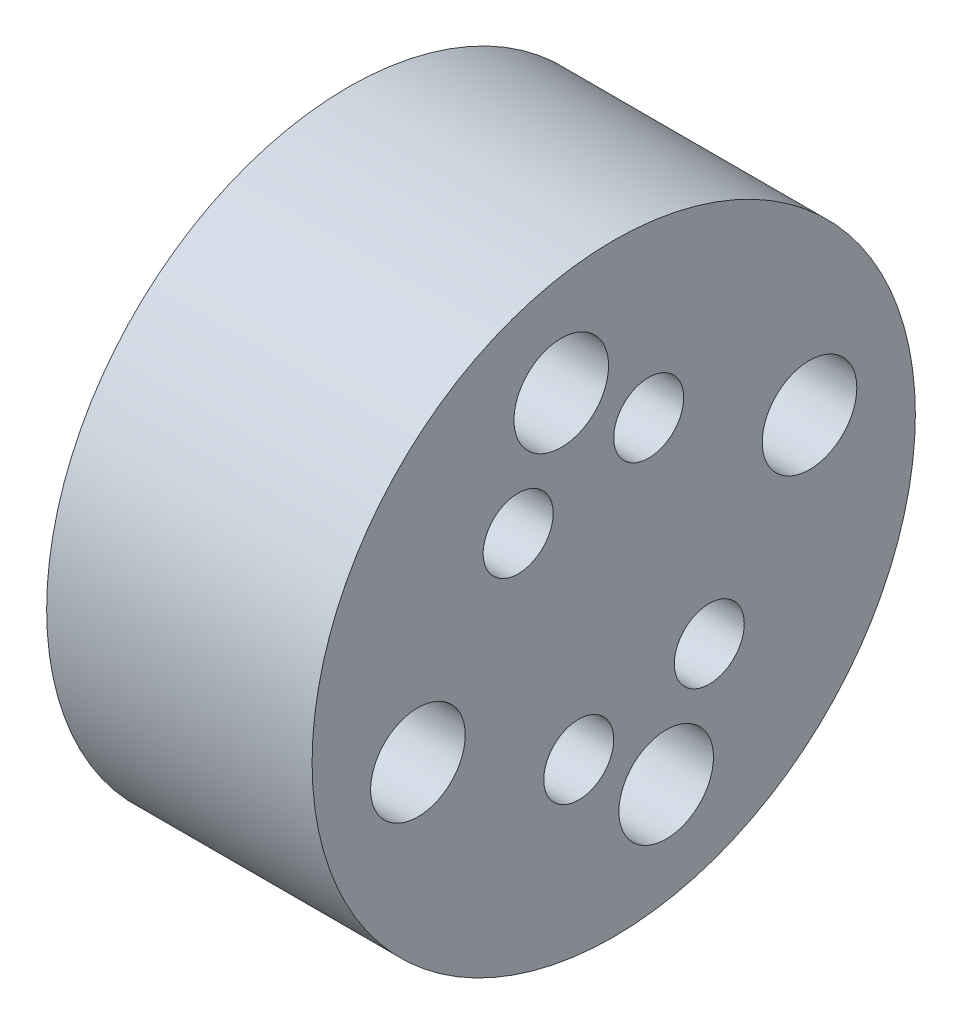
SolidWorks part; units mm, degrees
material "PLA"
ref_plane "Front Plane" through (0, 0, 0) normal (0, 0, 1) x (1, 0, 0)
ref_plane "Top Plane" through (0, 0, 0) normal (0, 1, 0) x (1, 0, 0)
ref_plane "Right Plane" through (0, 0, 0) normal (1, 0, 0) x (0, 0, -1)
sketch "Sketch1" plane through (0, 0, 0) normal (1, 0, 0) x (0, 0, -1)
  circle A0 centre (0, 0) radius 31.25
  dimension "D1" = 62.5
extrude "Boss-Extrude1" add sketch "Sketch1" along normal blind 23
sketch "Sketch6" plane through (23, 0, 0) normal (1, 0, 0) x (0, 0, -1)
  line L0 (-5.4352, 20.2844) -> (0, 0) construction
  line L1 (0, 0) -> (0, 21) construction
  circle A0 centre (0, 0) radius 21 construction
  circle A1 centre (-5.4352, 20.2844) radius 4
  circle A2 centre (0, 0) radius 21 construction
  circle A3 centre (20.2844, 5.4352) radius 4
  circle A4 centre (0, 0) radius 21 construction
  circle A5 centre (5.4352, -20.2844) radius 4
  circle A6 centre (0, 0) radius 21 construction
  circle A7 centre (-20.2844, -5.4352) radius 4
  point P18 (0, 0)
  dimension "D1" = 42
  dimension "D2" = 8
  dimension "D3" = 15
  dimension "D4" = 4
extrude "Cut-Extrude3" cut sketch "Sketch6" against normal through all
sketch "Sketch7" plane through (23, 0, 0) normal (1, 0, 0) x (0, 0, -1)
  circle A0 centre (-5.4352, 20.2844) radius 4.9
  circle A1 centre (20.2844, 5.4352) radius 4.9
  circle A2 centre (5.4352, -20.2844) radius 4.9
  circle A3 centre (-20.2844, -5.4352) radius 4.9
  dimension "D1" = 9.8
  dimension "D2" = 9.8
  dimension "D3" = 9.8
  dimension "D4" = 9.8
extrude "Cut-Extrude4" cut sketch "Sketch7" against normal blind 11.5
sketch "Sketch2" plane through (23, 0, 0) normal (1, 0, 0) x (0, 0, -1)
  line L0 (-9.8995, 9.8995) -> (0, 0) construction
  line L1 (0, 0) -> (0, 14) construction
  circle A0 centre (0, 0) radius 14 construction
  circle A1 centre (-9.8995, 9.8995) radius 2.125
  circle A2 centre (3.6235, 13.523) radius 2.125
  circle A3 centre (13.523, 3.6235) radius 2.125
  circle A4 centre (9.8995, -9.8995) radius 2.125
  circle A5 centre (-3.6235, -13.523) radius 2.125
  circle A6 centre (-13.523, -3.6235) radius 2.125
  point P19 (0, 0)
  dimension "D1" = 28
  dimension "D2" = 4.25
  dimension "D3" = 45
  dimension "D4" = 6
extrude "Cut-Extrude2" cut sketch "Sketch2" against normal through all contours A1 | A2 | A4 | A5
sketch "Sketch8" plane through (23, 0, 0) normal (1, 0, 0) x (0, 0, -1)
  circle A0 centre (-9.8995, 9.8995) radius 2.85
  circle A2 centre (3.6235, 13.523) radius 2.85
  circle A3 centre (13.523, 3.6235) radius 2.85
  circle A4 centre (9.8995, -9.8995) radius 2.85
  circle A5 centre (-3.6235, -13.523) radius 2.85
  circle A6 centre (-13.523, -3.6235) radius 2.85
  circle A7 centre (0, 0) radius 21 construction
  point P17 (0, 0)
  circle M2 centre (-3.6235, -13.523) radius 2.125
  circle M3 centre (9.8995, -9.8995) radius 2.125
  circle M5 centre (3.6235, 13.523) radius 2.125
  circle M6 centre (-9.8995, 9.8995) radius 2.125
  dimension "D1" = 5.7
  dimension "D2" = 6
extrude "Cut-Extrude5" cut sketch "Sketch8" against normal blind 14.5 contours A0 M6 | M6 | A2 M5 | M5 | M3 | A4 M3 | M2 | A5 M2
sketch "Sketch9" plane through (23, 0, 0) normal (1, 0, 0) x (0, 0, -1)
  circle A0 centre (-9.8995, 9.8995) radius 3.625
  circle A1 centre (3.6235, 13.523) radius 3.625
  circle A2 centre (9.8995, -9.8995) radius 3.625
  circle A3 centre (-3.6235, -13.523) radius 3.625
  circle A4 centre (-3.6235, -13.523) radius 2.125 construction
  circle A5 centre (3.6235, 13.523) radius 2.125 construction
  circle A6 centre (9.8995, -9.8995) radius 2.125 construction
  dimension "D1" = 7.25
  dimension "D2" = 7.25
  dimension "D3" = 7.25
  dimension "D4" = 7.25
extrude "Cut-Extrude6" cut sketch "Sketch9" against normal blind 5
sketch "Sketch10" plane through (23, 0, 0) normal (1, 0, 0) x (0, 0, -1)
  circle A1 centre (-3.6235, -13.523) radius 3.625
  circle A2 centre (-3.6235, -13.523) radius 3.625
  circle A3 centre (-9.8995, 9.8995) radius 3.625
  circle A4 centre (-9.8995, 9.8995) radius 3.625
  circle A5 centre (-5.4352, 20.2844) radius 4.9
  circle A6 centre (-5.4352, 20.2844) radius 4.9
  circle A7 centre (20.2844, 5.4352) radius 4.9
  circle A8 centre (20.2844, 5.4352) radius 4.9
  circle A9 centre (5.4352, -20.2844) radius 4.9
  circle A10 centre (5.4352, -20.2844) radius 4.9
  circle A11 centre (-20.2844, -5.4352) radius 4.9
  circle A12 centre (-20.2844, -5.4352) radius 4.9
  circle A13 centre (3.6235, 13.523) radius 3.625
  circle A14 centre (3.6235, 13.523) radius 3.625
  circle A15 centre (9.8995, -9.8995) radius 3.625
  circle A16 centre (9.8995, -9.8995) radius 3.625
  circle A17 centre (0, 0) radius 31.25
  circle A18 centre (0, 0) radius 31.25
  dimension "D1" = 0
  dimension "D2" = 0
  dimension "D3" = 0
  dimension "D4" = 0
  dimension "D5" = 0
  dimension "D6" = 0
  dimension "D7" = 0
  dimension "D8" = 0
  dimension "D9" = 0
extrude "Boss-Extrude2" add sketch "Sketch10" along normal blind 4.5
